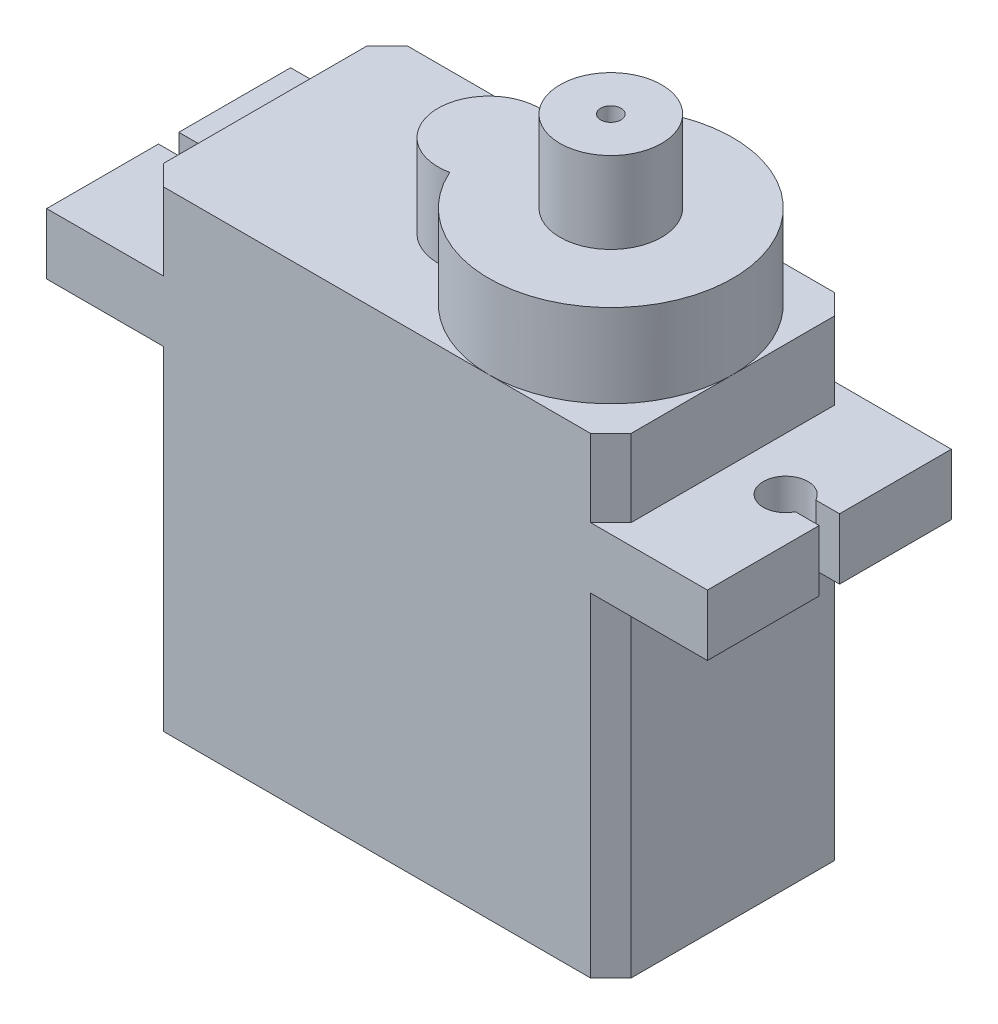
SolidWorks part; units mm, degrees
ref_plane "Alzado" through (0, 0, 0) normal (0, 0, 1) x (1, 0, 0)
ref_plane "Planta" through (0, 0, 0) normal (0, 1, 0) x (1, 0, 0)
ref_plane "Vista lateral" through (0, 0, 0) normal (1, 0, 0) x (0, 0, -1)
sketch "Croquis1" plane through (0, 0, 0) normal (0, 1, 0) x (1, 0, 0)
  line L1 (11.5, 6) -> (-11.5, 6)
  line L2 (11.5, 6) -> (11.5, -6)
  line L3 (11.5, -6) -> (-11.5, -6)
  line L4 (-11.5, 6) -> (-11.5, -6)
  line L5 (11.5, 6) -> (-11.5, -6) construction
  line L6 (11.5, -6) -> (-11.5, 6) construction
  point P0 (0, 0)
  dimension "D1" = 23
  dimension "D2" = 12
extrude "Saliente-Extruir1" add sketch "Croquis1" along normal blind 23.2
sketch "Croquis6" plane through (0, 0, 0) normal (0, -1, 0) x (1, 0, 0)
  circle A0 centre (-11.5, 6) radius 2
  circle A1 centre (11.5, 6) radius 2
  circle A2 centre (-11.5, -6) radius 2
  circle A3 centre (11.5, -6) radius 2
extrude "Cortar-Extruir1" cut sketch "Croquis6" against normal blind 0.5
sketch "Croquis7" plane through (0, 23.2, 0) normal (0, 1, 0) x (1, 0, 0)
  line L0 (11.5, -6) -> (11.5, 6) construction
  arc A0 (0.0208, -2.4451) -> (0.0208, 2.4451) centre (5.5, 0) ccw
  arc A1 (0.0208, 2.4451) -> (0.0208, -2.4451) centre (-0.5, 0) ccw
extrude "Saliente-Extruir3" add sketch "Croquis7" along normal blind 4.1
sketch "Croquis8" plane through (0, 27.3, 0) normal (0, 1, 0) x (1, 0, 0)
  circle A0 centre (5.5, 0) radius 2.5
  arc A1 (0.0208, -2.4451) -> (0.0208, 2.4451) centre (5.5, 0) ccw construction
  point P5 (0, 0)
  dimension "D1" = 0
extrude "Saliente-Extruir4" add sketch "Croquis8" along normal blind 4
sketch "Croquis9" plane through (0, 31.3, 0) normal (0, 1, 0) x (1, 0, 0)
  circle A0 centre (5.5, 0) radius 0.5
  circle A1 centre (5.5, 0) radius 2.5 construction
  dimension "D2" = 1
  dimension "D1" = 0
extrude "Cortar-Extruir2" cut sketch "Croquis9" against normal blind 4
ref_plane "Plano1" through (0, 0, 0) normal (-1, 0, 0) x (0, 0, 1)
sketch "Croquis11" plane through (-11.5, 0, 0) normal (-1, 0, 0) x (0, 0, 1)
  line L0 (-6, 23.2) -> (-6, 0.5) construction
  line L1 (-6, 19.3999) -> (6, 19.3999)
  line L2 (-6, 19.3999) -> (-6, 16.3999)
  line L3 (-6, 16.3999) -> (6, 16.3999)
  line L4 (6, 19.3999) -> (6, 16.3999)
  line L5 (6, 23.2) -> (6, 0.5) construction
  line L6 (-4, 0) -> (4, 0) construction
  dimension "D1" = 16.3999
  dimension "D2" = 3
extrude "Saliente-Extruir5" add sketch "Croquis11" along normal blind 4.75
sketch "Croquis12" plane through (0, 19.3999, 0) normal (0, 1, 0) x (1, 0, 0)
  line L0 (-11.5, -6) -> (-11.5, 6) construction
  line L1 (-16.25, -6) -> (-16.25, 6) construction
  line L2 (-16.25, 0.5) -> (-15.0798, 0.5)
  line L3 (-16.25, 0.5) -> (-16.25, -0.5)
  line L4 (-16.25, -0.5) -> (-15.0798, -0.5)
  line L6 (-16.25, -6) -> (-11.5, -6) construction
  arc A0 (-15.0798, -0.5) -> (-15.0798, 0.5) centre (-14.1, 0) ccw
  point P10 (0, 0)
  dimension "D1" = 2.6
  dimension "D3" = 6
  dimension "D4" = 0.5
extrude "Cortar-Extruir3" cut sketch "Croquis12" against normal up to surface (3 mm away) up to face at (-13.875, 16.3999, 0)
mirror "Simetría1" about plane through (0, 0, 0) normal (-1, 0, 0) of "Saliente-Extruir5", "Saliente-Extruir1", "Cortar-Extruir3"
chamfer "Chaflán3" distance 1 angle 45 6 edges at (11.5, 21.2999, -6) (11.5, 21.2999, 6) (-11.5, 8.1999, -6) (-11.5, 8.1999, 6) (-11.5, 21.2999, 6) (-11.5, 21.2999, -6)
